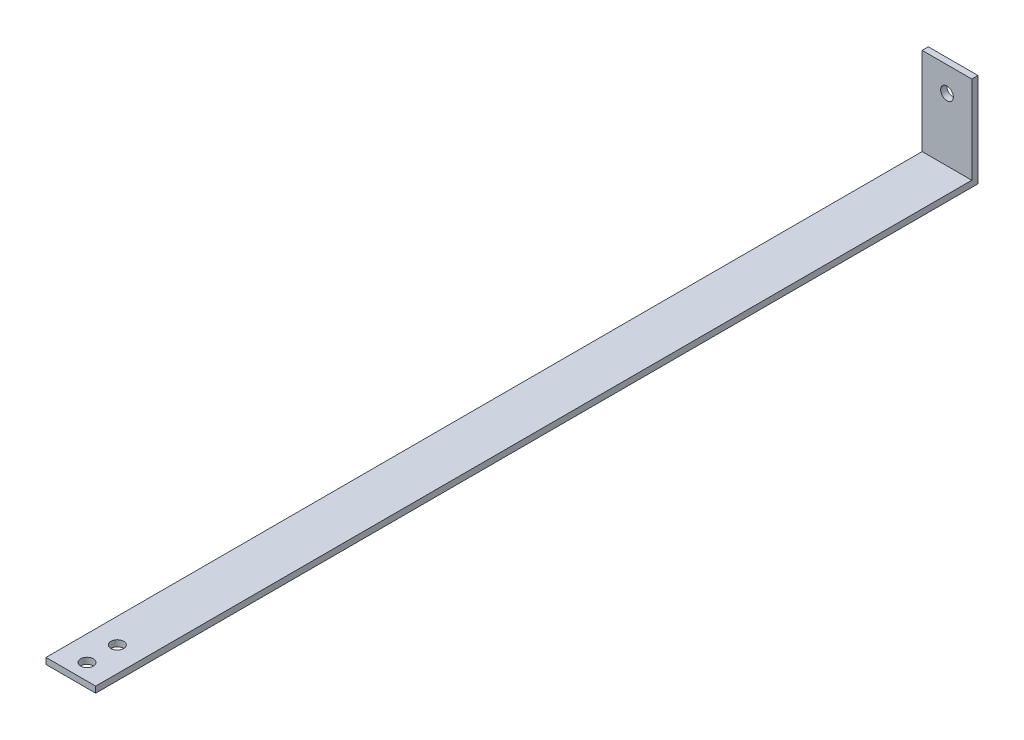
SolidWorks part; units mm, degrees
ref_plane "Alzado" through (0, 0, 0) normal (0, 0, 1) x (1, 0, 0)
ref_plane "Planta" through (0, 0, 0) normal (0, 1, 0) x (1, 0, 0)
ref_plane "Vista lateral" through (0, 0, 0) normal (1, 0, 0) x (0, 0, -1)
sketch "Croquis1" plane through (0, 0, 0) normal (1, 0, 0) x (0, 0, -1)
  line L0 (-6.31, 95.93) -> (0, 95.93)
  line L1 (0, 95.93) -> (0, 0)
  line L2 (0, 0) -> (-902.2, 0)
  line L3 (-902.2, 0) -> (-902.2, 6.31)
  line L4 (-902.2, 6.31) -> (-6.31, 6.31)
  line L5 (-6.31, 6.31) -> (-6.31, 95.93)
  dimension "D1" = 902.2
  dimension "D2" = 6.31
  dimension "D3" = 95.93
  dimension "D4" = 6.31
extrude "Saliente-Extruir1" add sketch "Croquis1" along normal blind 50.8
sketch "Croquis2" plane through (0, 0, 0) normal (0, -1, 0) x (-1, 0, 0)
  line L0 (-25.4, -902.2) -> (-25.4, -885.7) construction
  line L1 (-50.8, -902.2) -> (0, -902.2) construction
  line L2 (-25.4, -885.7) -> (-25.4, -854.7) construction
  circle A0 centre (-25.4, -885.7) radius 6.5
  circle A1 centre (-25.4, -854.7) radius 6.5
  dimension "D1" = 13
  dimension "D2" = 13
extrude "Cortar-Extruir1" cut sketch "Croquis2" against normal blind 10
sketch "Croquis3" plane through (0, 0, 0) normal (0, 0, -1) x (-1, 0, 0)
  line L0 (-25.4, 95.93) -> (-25.4, 70.53) construction
  line L1 (-50.8, 95.93) -> (0, 95.93) construction
  circle A0 centre (-25.4, 70.53) radius 6.5
  dimension "D2" = 13
  dimension "D1" = 25.4
extrude "Cortar-Extruir2" cut sketch "Croquis3" against normal blind 10
